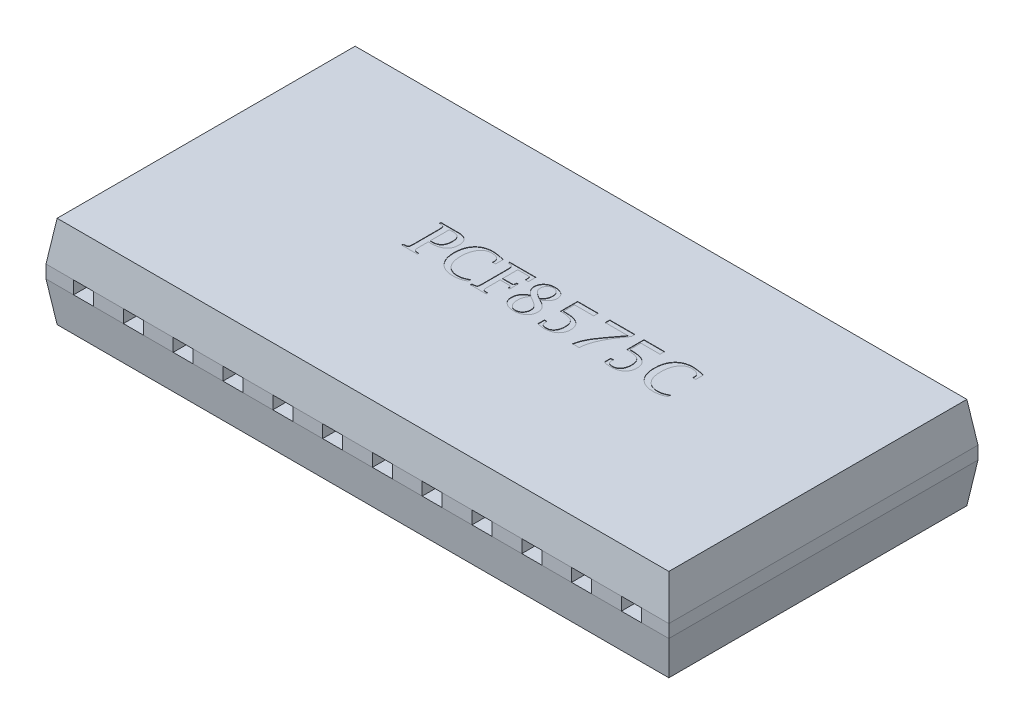
SolidWorks part; units mm, degrees
ref_plane "Front Plane" through (0, 0, 0) normal (0, 0, 1) x (1, 0, 0)
ref_plane "Top Plane" through (0, 0, 0) normal (0, 1, 0) x (1, 0, 0)
ref_plane "Right Plane" through (0, 0, 0) normal (1, 0, 0) x (0, 0, -1)
sketch "Sketch1" plane through (0, 0, 0) normal (0, 1, 0) x (1, 0, 0)
  line L1 (-7.8, 3.8) -> (7.8, 3.8)
  line L2 (-7.8, 3.8) -> (-7.8, -3.8)
  line L3 (-7.8, -3.8) -> (7.8, -3.8)
  line L4 (7.8, 3.8) -> (7.8, -3.8)
  line L5 (-7.8, 3.8) -> (7.8, -3.8) construction
  line L6 (-7.8, -3.8) -> (7.8, 3.8) construction
  point P0 (0, 0)
  dimension "D1" = 15.6
  dimension "D2" = 7.6
extrude "Boss-Extrude1" add sketch "Sketch1" along normal blind 1.01 draft 8 draft outward yes
sketch "Sketch2" plane through (0, 1.01, 0) normal (0, 1, 0) x (1, 0, 0)
  line L4 (7.9419, -3.9419) -> (7.9419, 3.9419)
  line L5 (7.9419, 3.9419) -> (-7.9419, 3.9419)
  line L6 (-7.9419, 3.9419) -> (-7.9419, -3.9419)
  line L7 (-7.9419, -3.9419) -> (7.9419, -3.9419)
  line L8 (7.9419, -3.9419) -> (7.9419, 3.9419)
  line L9 (7.9419, 3.9419) -> (-7.9419, 3.9419)
  line L10 (-7.9419, 3.9419) -> (-7.9419, -3.9419)
  line L11 (-7.9419, -3.9419) -> (7.9419, -3.9419)
  dimension "D1" = 0
extrude "Boss-Extrude2" add sketch "Sketch2" along normal blind 0.33
sketch "Sketch3" plane through (0, 1.34, 0) normal (0, 1, 0) x (1, 0, 0)
  line L4 (-7.9419, -3.9419) -> (7.9419, -3.9419)
  line L5 (7.9419, -3.9419) -> (7.9419, 3.9419)
  line L6 (7.9419, 3.9419) -> (-7.9419, 3.9419)
  line L7 (-7.9419, 3.9419) -> (-7.9419, -3.9419)
  line L8 (-7.9419, -3.9419) -> (7.9419, -3.9419)
  line L9 (7.9419, -3.9419) -> (7.9419, 3.9419)
  line L10 (7.9419, 3.9419) -> (-7.9419, 3.9419)
  line L11 (-7.9419, 3.9419) -> (-7.9419, -3.9419)
  dimension "D1" = 0
extrude "Boss-Extrude3" add sketch "Sketch3" along normal blind 1.01 draft 8
sketch "Sketch4" plane through (0, 0, 3.9419) normal (0, 0, 1) x (1, 0, 0)
  line L0 (0, 3.9145) -> (0, -2.2322) construction
  line L1 (-7.9419, 1.34) -> (7.9419, 1.34) construction
  line L2 (6.7319, 1.34) -> (7.2419, 1.34)
  line L3 (6.7319, 1.34) -> (6.7319, 1.01)
  line L4 (6.7319, 1.01) -> (7.2419, 1.01)
  line L5 (7.2419, 1.34) -> (7.2419, 1.01)
  line L6 (-7.9419, 1.01) -> (7.9419, 1.01) construction
  line L7 (7.9419, 1.34) -> (7.9419, 1.01) construction
  line L8 (5.4619, 1.34) -> (5.4619, 1.01)
  line L9 (5.4619, 1.34) -> (5.9719, 1.34)
  line L10 (5.9719, 1.34) -> (5.9719, 1.01)
  line L11 (5.4619, 1.01) -> (5.9719, 1.01)
  line L12 (4.1919, 1.34) -> (4.1919, 1.01)
  line L13 (4.1919, 1.34) -> (4.7019, 1.34)
  line L14 (4.7019, 1.34) -> (4.7019, 1.01)
  line L15 (4.1919, 1.01) -> (4.7019, 1.01)
  line L16 (2.9219, 1.34) -> (2.9219, 1.01)
  line L17 (2.9219, 1.34) -> (3.4319, 1.34)
  line L18 (3.4319, 1.34) -> (3.4319, 1.01)
  line L19 (2.9219, 1.01) -> (3.4319, 1.01)
  line L20 (1.6519, 1.34) -> (1.6519, 1.01)
  line L21 (1.6519, 1.34) -> (2.1619, 1.34)
  line L22 (2.1619, 1.34) -> (2.1619, 1.01)
  line L23 (1.6519, 1.01) -> (2.1619, 1.01)
  line L24 (0.3819, 1.34) -> (0.3819, 1.01)
  line L25 (0.3819, 1.34) -> (0.8919, 1.34)
  line L26 (0.8919, 1.34) -> (0.8919, 1.01)
  line L27 (0.3819, 1.01) -> (0.8919, 1.01)
  line L28 (-0.8881, 1.34) -> (-0.8881, 1.01)
  line L29 (-0.8881, 1.34) -> (-0.3781, 1.34)
  line L30 (-0.3781, 1.34) -> (-0.3781, 1.01)
  line L31 (-0.8881, 1.01) -> (-0.3781, 1.01)
  line L32 (-2.1581, 1.34) -> (-2.1581, 1.01)
  line L33 (-2.1581, 1.34) -> (-1.6481, 1.34)
  line L34 (-1.6481, 1.34) -> (-1.6481, 1.01)
  line L35 (-2.1581, 1.01) -> (-1.6481, 1.01)
  line L36 (-3.4281, 1.34) -> (-3.4281, 1.01)
  line L37 (-3.4281, 1.34) -> (-2.9181, 1.34)
  line L38 (-2.9181, 1.34) -> (-2.9181, 1.01)
  line L39 (-3.4281, 1.01) -> (-2.9181, 1.01)
  line L40 (-4.6981, 1.34) -> (-4.6981, 1.01)
  line L41 (-4.6981, 1.34) -> (-4.1881, 1.34)
  line L42 (-4.1881, 1.34) -> (-4.1881, 1.01)
  line L43 (-4.6981, 1.01) -> (-4.1881, 1.01)
  line L44 (-5.9681, 1.34) -> (-5.9681, 1.01)
  line L45 (-5.9681, 1.34) -> (-5.4581, 1.34)
  line L46 (-5.4581, 1.34) -> (-5.4581, 1.01)
  line L47 (-5.9681, 1.01) -> (-5.4581, 1.01)
  line L48 (-7.2381, 1.34) -> (-7.2381, 1.01)
  line L49 (-7.2381, 1.34) -> (-6.7281, 1.34)
  line L50 (-6.7281, 1.34) -> (-6.7281, 1.01)
  line L51 (-7.2381, 1.01) -> (-6.7281, 1.01)
  point P13 (7.9419, 1.175)
  dimension "D1" = 0.51
  dimension "D2" = 0.7
  dimension "D3" = 12
extrude "Cut-Extrude1" cut sketch "Sketch4" against normal blind 9.01
sketch "Sketch5" plane through (0, 2.35, 0) normal (0, 1, 0) x (1, 0, 0)
  line L0 (-5.9786, 0) -> (7.1452, 0) construction
  text T0 "PCF8575C" font "Lucida Bright" height 1
extrude "Cut-Extrude2" cut sketch "Sketch5" against normal blind 0.01
